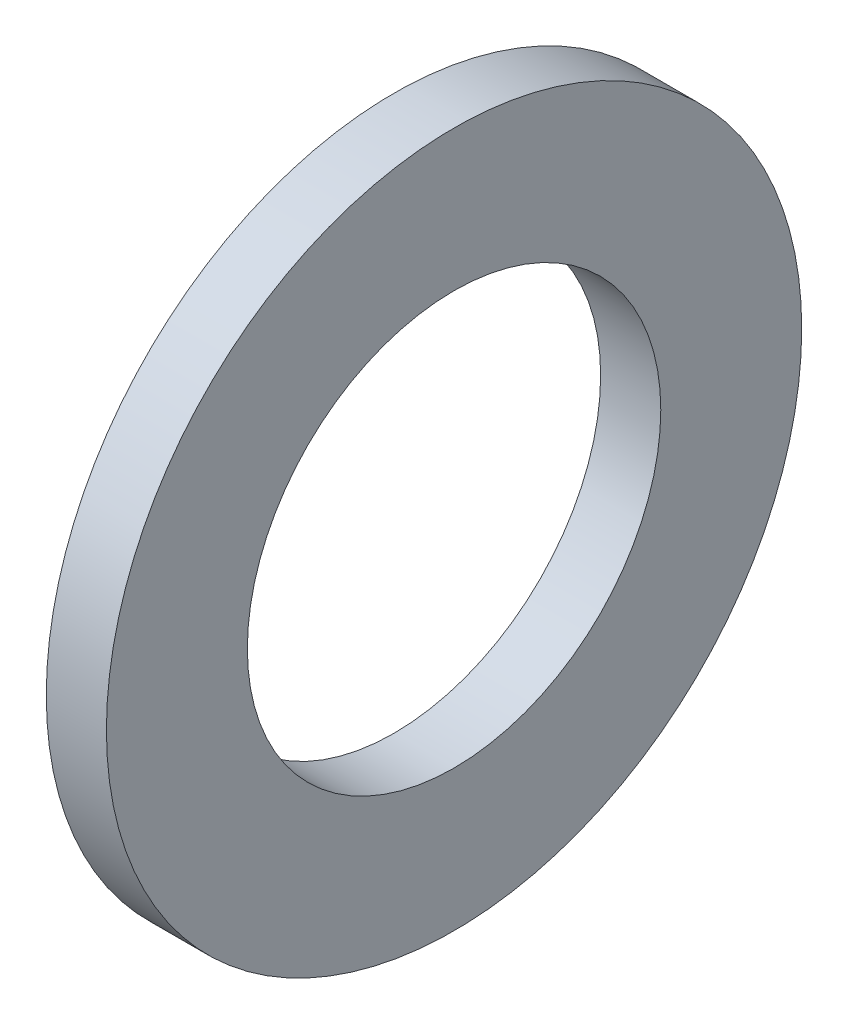
SolidWorks part; units mm, degrees
ref_plane "Plane1" through (0, 0, 0) normal (0, 0, 1) x (1, 0, 0)
ref_plane "Plane2" through (0, 0, 0) normal (0, 1, 0) x (1, 0, 0)
ref_plane "Plane3" through (0, 0, 0) normal (1, 0, 0) x (0, 0, -1)
sketch "Sketch1" plane through (0, 0, 0) normal (0, 0, 1) x (1, 0, 0)
  line L0 (-34.925, 0) -> (9.525, 0) construction
  line L1 (0, 11) -> (0, 18.5)
  line L2 (0, 18.5) -> (-3.2, 18.5)
  line L3 (-3.2, 18.5) -> (-3.2, 11)
  line L4 (-3.2, 11) -> (0, 11)
  dimension "Thickness" = 3.2
  dimension "Inside_dia" = 22
  dimension "Outside_dia" = 37
revolve "Base-Revolve" add sketch "Sketch1" angle 360 about L0
